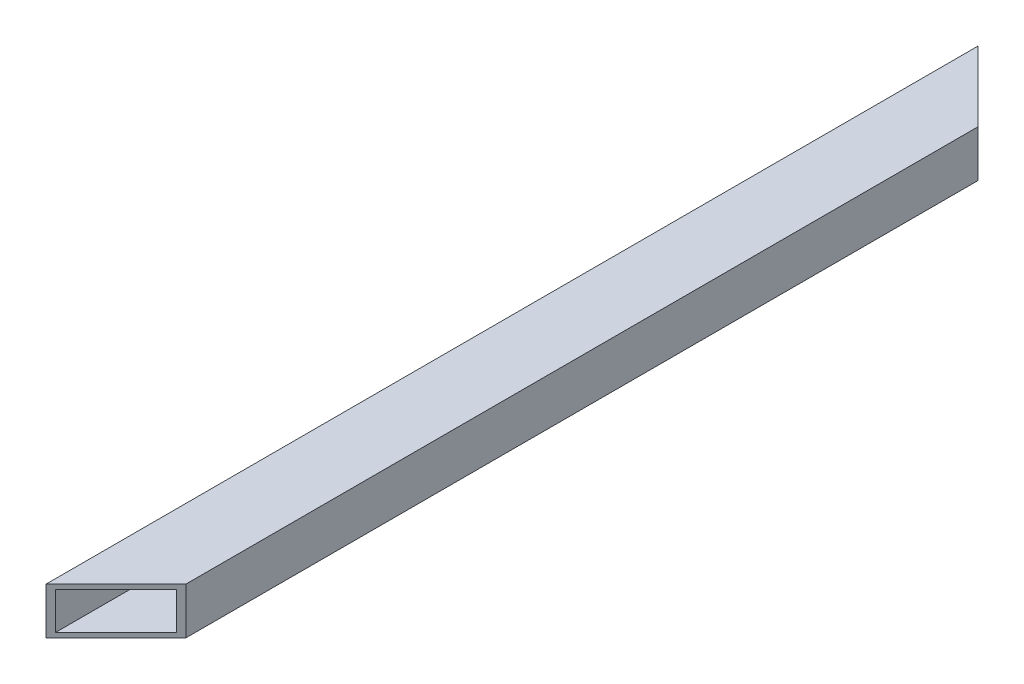
SolidWorks part; units mm, degrees
material "Ferro duttile"
ref_plane "Piano frontale" through (0, 0, 0) normal (0, 0, 1) x (1, 0, 0)
ref_plane "Piano superiore" through (0, 0, 0) normal (0, 1, 0) x (1, 0, 0)
ref_plane "Piano destro" through (0, 0, 0) normal (1, 0, 0) x (0, 0, -1)
sketch "Schizzo1" plane through (0, 0, 0) normal (0, 0, 1) x (1, 0, 0)
  line L1 (13, -8) -> (-13, -8)
  line L2 (13, -8) -> (13, 8)
  line L3 (13, 8) -> (-13, 8)
  line L4 (-13, -8) -> (-13, 8)
  line L5 (13, -8) -> (-13, 8) construction
  line L6 (13, 8) -> (-13, -8) construction
  line L7 (15, -10) -> (-15, -10)
  line L8 (15, -10) -> (15, 10)
  line L9 (15, 10) -> (-15, 10)
  line L10 (-15, -10) -> (-15, 10)
  line L11 (15, -10) -> (-15, 10) construction
  line L12 (15, 10) -> (-15, -10) construction
  point P0 (0, 0)
  point P6 (0, 0)
  point P11 (-15, 0)
  dimension "D1" = 20
  dimension "D2" = 30
  dimension "D3" = 2
  dimension "D4" = 2
extrude "Estrusione-Estrusione1" add sketch "Schizzo1" along normal blind 400
sketch "Schizzo2" plane through (0, 10, 0) normal (0, 1, 0) x (1, 0, 0)
  line L0 (-15, 0) -> (15, -30)
  line L1 (15, -400) -> (15, 0) construction
  line L2 (15, 0) -> (-15, 0) construction
  line L3 (-15, 0) -> (15, 0)
  line L4 (15, 0) -> (15, -30)
  line L5 (-15, -400) -> (15, -370)
  line L6 (15, -370) -> (15, -400)
  line L7 (15, -400) -> (-15, -400)
  dimension "D1" = 45
  dimension "D2" = 45
extrude "Taglio-Estrusione1" cut sketch "Schizzo2" against normal through all
